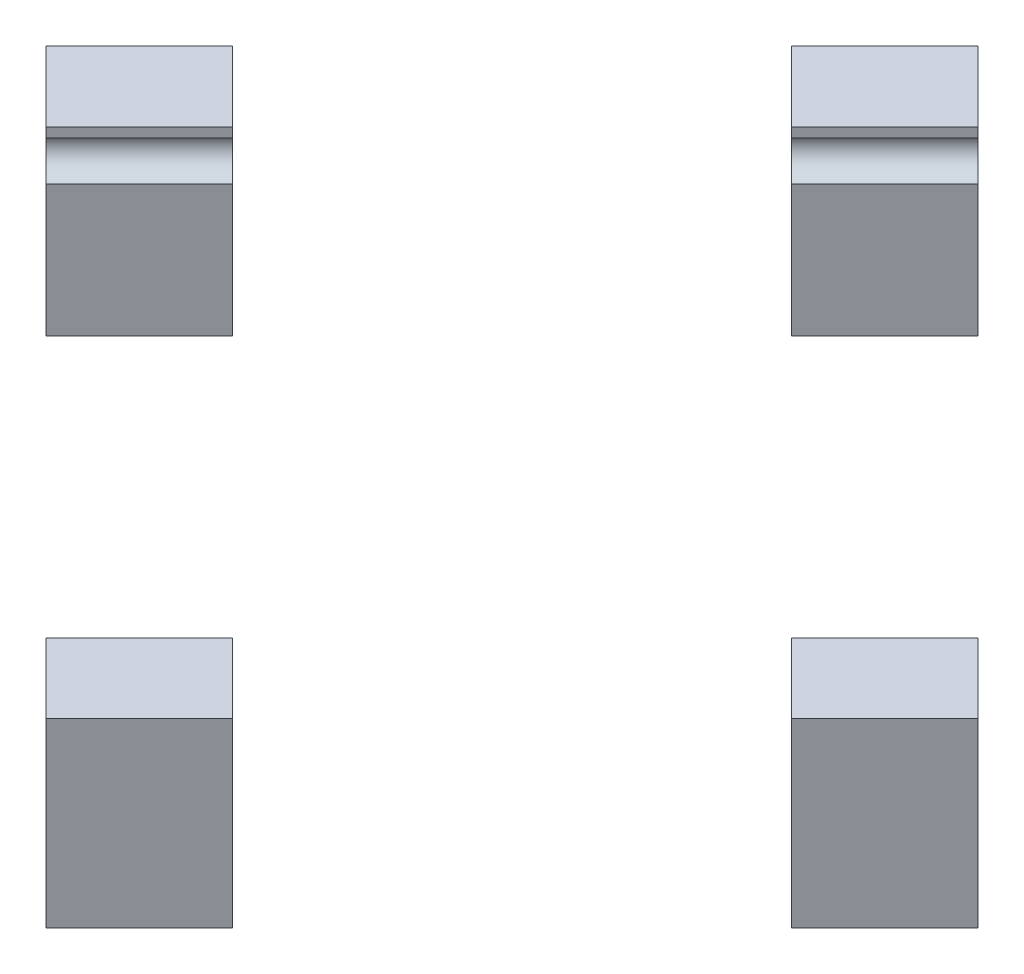
SolidWorks part; units mm, degrees
ref_plane "Front Plane" through (0, 0, 0) normal (0, 0, 1) x (1, 0, 0)
ref_plane "Top Plane" through (0, 0, 0) normal (0, 1, 0) x (1, 0, 0)
ref_plane "Right Plane" through (0, 0, 0) normal (1, 0, 0) x (0, 0, -1)
sketch "Sketch5" plane through (0, 0, 0) normal (0, 1, 0) x (1, 0, 0)
  line L0 (9.585, -5.3822) -> (12.4134, -2.5538)
  line L1 (12.4134, -2.5538) -> (10.2921, -0.4325)
  line L2 (10.2921, -0.4325) -> (7.4637, -3.2609)
  line L3 (9.585, -5.3822) -> (7.4637, -3.2609)
  line L6 (-5.9714, 10.1741) -> (-3.1429, 13.0026)
  line L7 (-3.1429, 13.0026) -> (-5.2642, 15.1239)
  line L8 (-5.2642, 15.1239) -> (-8.0927, 12.2955)
  line L9 (-8.0927, 12.2955) -> (-5.9714, 10.1741)
  line L10 (-17.2851, -1.1396) -> (-14.4566, 1.6889)
  line L11 (-14.4566, 1.6889) -> (-16.578, 3.8102)
  line L12 (-16.578, 3.8102) -> (-19.4064, 0.9818)
  line L13 (-19.4064, 0.9818) -> (-17.2851, -1.1396)
  line L14 (-1.7287, -16.6959) -> (1.0997, -13.8675)
  line L15 (1.0997, -13.8675) -> (-1.0216, -11.7462)
  line L16 (-1.0216, -11.7462) -> (-3.85, -14.5746)
  line L17 (-3.85, -14.5746) -> (-1.7287, -16.6959)
  dimension "D1" = 3
  dimension "D2" = 4
  dimension "D3" = 19
  dimension "D4" = 12
  dimension "D5" = 4
  dimension "D6" = 3
  dimension "D7" = 12
  dimension "D8" = 3
  dimension "D9" = 4
  dimension "D11" = 3
  dimension "D12" = 4
extrude "Boss-Extrude3" add sketch "Sketch5" along normal blind 5.5
ref_plane "Plane3" through (4.9298, 0, -4.9298) normal (0.7071, 0, -0.7071) x (-0.7071, 0, -0.7071)
sketch "Sketch6" plane through (4.9298, 0, -4.9298) normal (0.7071, 0, -0.7071) x (-0.7071, 0, -0.7071)
  line L1 (-7.5834, 5.5) -> (-7.5834, 0) construction
  arc A0 (-7.5834, 5.2) -> (-7.5834, 4) centre (-7.5834, 4.6) ccw
  dimension "D1" = 0.6
  dimension "D2" = 4
  dimension "D3" = 0
extrude "Cut-Extrude2" cut sketch "Sketch6" against normal through all and the other way through all
ref_plane "Plane4" through (4.9298, 0, -4.9298) normal (0.7071, 0, -0.7071) x (-0.7071, 0, -0.7071)
sketch "Sketch7" plane through (4.9298, 0, -4.9298) normal (0.7071, 0, -0.7071) x (-0.7071, 0, -0.7071)
  line L0 (11.4166, 5.5) -> (11.4166, 0) construction
  line L1 (11.4166, 5.2) -> (11.4166, 4)
  arc A0 (11.4166, 5.2) -> (11.4166, 4) centre (11.4166, 4.6) cw
  dimension "D1" = 0.6
  dimension "D2" = 4
  dimension "D3" = 0
extrude "Cut-Extrude5" cut sketch "Sketch7" against normal through all
